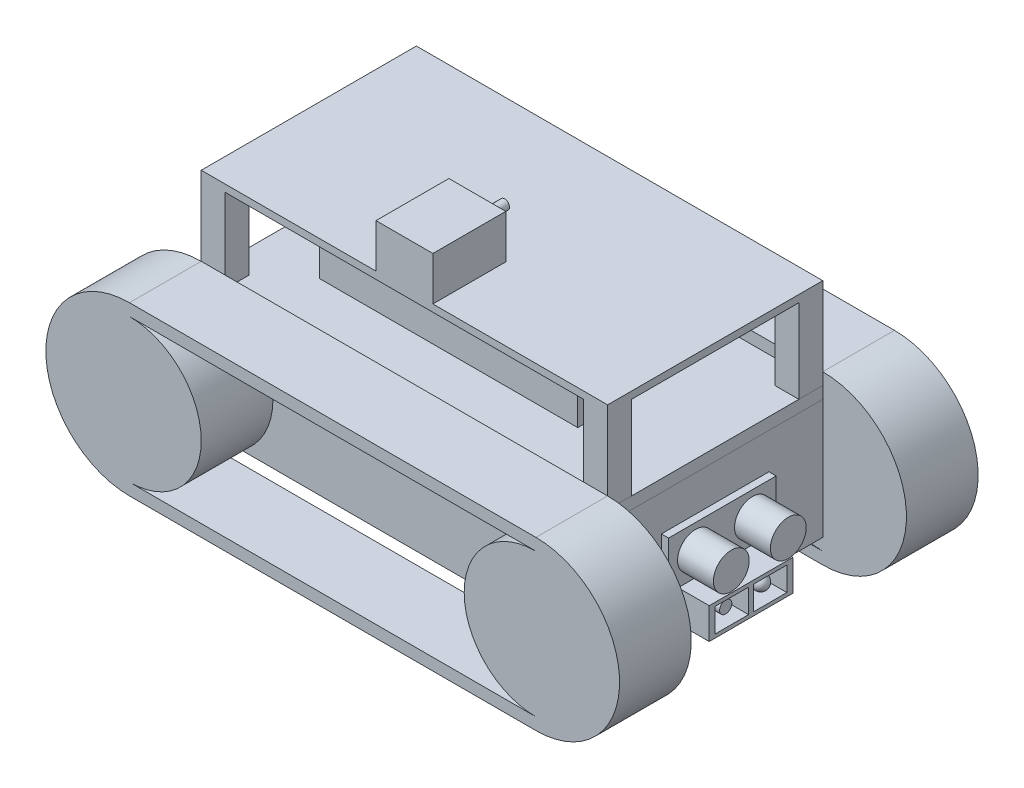
SolidWorks part; units mm, degrees
ref_plane "Front Plane" through (0, 0, 0) normal (0, 0, 1) x (1, 0, 0)
ref_plane "Top Plane" through (0, 0, 0) normal (0, 1, 0) x (1, 0, 0)
ref_plane "Right Plane" through (0, 0, 0) normal (1, 0, 0) x (0, 0, -1)
sketch "Sketch1" plane through (0, 0, 0) normal (0, 1, 0) x (1, 0, 0)
  line L1 (0, 0) -> (170, 0)
  line L2 (0, 0) -> (0, 90)
  line L3 (0, 90) -> (170, 90)
  line L4 (170, 0) -> (170, 90)
  dimension "D1" = 170
  dimension "D2" = 90
extrude "Boss-Extrude1" add sketch "Sketch1" along normal blind 50 contours L3 L4 L1 L2
sketch "Sketch2" plane through (0, 0, 0) normal (0, 0, 1) x (1, 0, 0)
  line L0 (170, 50) -> (170, 0) construction
  line L1 (0, 50) -> (0, 0) construction
  circle A0 centre (170, 25) radius 30
  circle A1 centre (0, 25) radius 30
  dimension "D1" = 60
  dimension "D2" = 60
extrude "Boss-Extrude2" add sketch "Sketch2" along normal blind 30
pattern_linear "LPattern1" count 2 spacing 120 along (0, 0, -1) of "Boss-Extrude2"
sketch "Sketch3" plane through (0, 0, 30) normal (0, 0, 1) x (1, 0, 0)
  line L0 (0, 60) -> (170, 60)
  line L1 (0, -10) -> (170, -10)
  line L2 (170, 55) -> (0, 55)
  line L3 (0, -5) -> (170, -5)
  circle A0 centre (170, 25) radius 35 construction
  circle A1 centre (0, 25) radius 35 construction
  circle A2 centre (0, 25) radius 30 construction
  circle A3 centre (170, 25) radius 30 construction
  arc A4 (170, 60) -> (170, -10) centre (170, 25) cw
  arc A5 (170, 55) -> (170, -5) centre (170, 25) cw
  arc A6 (0, 60) -> (0, -10) centre (0, 25) ccw
  arc A7 (0, -5) -> (0, 55) centre (0, 25) cw
  dimension "D1" = 70
  dimension "D2" = 70
extrude "Boss-Extrude3" add sketch "Sketch3" against normal blind 30
pattern_linear "LPattern2" count 2 spacing 120 along (0, 0, -1) of "Boss-Extrude3"
sketch "Sketch4" plane through (0, 50, 0) normal (0, 1, 0) x (1, 0, 0)
  line L1 (0, 90) -> (170, 90)
  line L2 (0, 90) -> (0, 0)
  line L3 (0, 0) -> (170, 0)
  line L4 (170, 90) -> (170, 0)
extrude "Boss-Extrude6" add sketch "Sketch4" along normal blind 5 separate body
sketch "Sketch5" plane through (0, 55, 0) normal (0, 1, 0) x (1, 0, 0)
  line L0 (85, 90) -> (85, 0)
  line L1 (170, 90) -> (0, 90) construction
  line L2 (170, 0) -> (0, 0) construction
  line L6 (31, 18.5) -> (139, 18.5) construction
  line L7 (31, 18.5) -> (31, 71.5) construction
  line L8 (31, 71.5) -> (139, 71.5) construction
  line L9 (139, 18.5) -> (139, 71.5) construction
  line L10 (31, 18.5) -> (139, 71.5)
  line L11 (31, 71.5) -> (139, 18.5)
  point P6 (85, 45)
  dimension "D1" = 53
  dimension "D2" = 108
ref_plane "Plane1" through (0, 60, 0) normal (0, 1, 0) x (1, 0, 0)
sketch "Sketch6" plane through (0, 60, 0) normal (0, 1, 0) x (1, 0, 0)
  line L1 (31, 71.5) -> (139, 71.5)
  line L2 (31, 71.5) -> (31, 18.5)
  line L3 (31, 18.5) -> (139, 18.5)
  line L4 (139, 71.5) -> (139, 18.5)
  line L5 (31, 71.5) -> (139, 18.5) construction
  line L6 (31, 18.5) -> (139, 71.5) construction
  point P0 (85, 45)
extrude "Boss-Extrude7" add sketch "Sketch6" along normal blind 15 separate body
ref_plane "Plane2" through (0, 90, 0) normal (0, 1, 0) x (1, 0, 0)
sketch "Sketch7" plane through (0, 90, 0) normal (0, 1, 0) x (1, 0, 0)
  line L0 (170, 0) -> (170, -30) construction
  line L1 (0, 90) -> (170, 90)
  line L2 (0, 90) -> (0, 0)
  line L3 (0, 0) -> (170, 0)
  line L4 (170, 90) -> (170, 0)
  line L5 (0, 90) -> (170, 0) construction
  line L6 (0, 0) -> (170, 90) construction
  line L7 (205, 0) -> (170, 0) construction
  point P0 (85, 45)
extrude "Boss-Extrude8" add sketch "Sketch7" along normal blind 3 separate body
sketch "Sketch8" plane through (0, 0, 0) normal (0, 0, 1) x (1, 0, 0)
  line L0 (85, 93) -> (85, 111.3) construction
  line L1 (0, 93) -> (170, 93) construction
  line L3 (73.1, 111.3) -> (96.9, 111.3)
  line L4 (73.1, 111.3) -> (73.1, 93)
  line L5 (73.1, 93) -> (96.9, 93)
  line L6 (96.9, 111.3) -> (96.9, 93)
  line L7 (73.1, 111.3) -> (96.9, 93) construction
  line L8 (73.1, 93) -> (96.9, 111.3) construction
  point P4 (85, 102.15)
  dimension "D1" = 18.3
  dimension "D2" = 23.8
extrude "Boss-Extrude9" add sketch "Sketch8" against normal blind 30.5
sketch "Sketch9" plane through (0, 0, -30.5) normal (0, 0, -1) x (-1, 0, 0)
  line L0 (-85, 111.3) -> (-85, 93) construction
  line L1 (-96.9, 111.3) -> (-73.1, 111.3) construction
  line L2 (-73.1, 93) -> (-96.9, 93) construction
  circle A0 centre (-85, 102.15) radius 2.0061
extrude "Boss-Extrude10" add sketch "Sketch9" along normal blind 11.45
sketch "Sketch10" plane through (170, 0, 0) normal (1, 0, 0) x (0, 0, -1)
  line L0 (45, 50) -> (45, 0) construction
  line L1 (0, 50) -> (90, 50) construction
  line L2 (0, 0) -> (90, 0) construction
  line L4 (22.5, 35) -> (67.5, 35)
  line L5 (22.5, 35) -> (22.5, 15)
  line L6 (22.5, 15) -> (67.5, 15)
  line L7 (67.5, 35) -> (67.5, 15)
  line L8 (22.5, 35) -> (67.5, 15) construction
  line L9 (22.5, 15) -> (67.5, 35) construction
  point P6 (45, 25)
  dimension "D1" = 20
  dimension "D2" = 45
extrude "Boss-Extrude11" add sketch "Sketch10" along normal blind 3
sketch "Sketch11" plane through (173, 0, 0) normal (1, 0, 0) x (0, 0, -1)
  line L0 (45, 35) -> (45, 15) construction
  line L1 (67.5, 35) -> (22.5, 35) construction
  line L2 (22.5, 15) -> (67.5, 15) construction
  line L3 (45, 25) -> (22.5, 25) construction
  line L4 (22.5, 35) -> (22.5, 15) construction
  line L5 (45, 25) -> (67.5, 25) construction
  line L6 (67.5, 15) -> (67.5, 35) construction
  circle A0 centre (57.5882, 25) radius 7.5
  circle A1 centre (33.75, 25) radius 7.5
  dimension "D1" = 15
  dimension "D2" = 15
extrude "Boss-Extrude12" add sketch "Sketch11" along normal blind 15
sketch "Sketch12" plane through (170, 0, 0) normal (1, 0, 0) x (0, 0, -1)
  line L0 (45, 15) -> (45, 0) construction
  line L1 (22.5, 15) -> (67.5, 15) construction
  line L2 (0, 0) -> (90, 0) construction
  line L3 (30, 12.5) -> (44, 12.5)
  line L4 (30, 12.5) -> (60, 12.5) construction
  line L5 (30, 12.5) -> (30, 2.5)
  line L6 (30, 2.5) -> (60, 2.5) construction
  line L7 (60, 12.5) -> (60, 2.5)
  line L8 (30, 12.5) -> (60, 2.5) construction
  line L9 (30, 2.5) -> (60, 12.5) construction
  line L10 (27.5, 14) -> (62.5, 14)
  line L11 (27.5, 14) -> (27.5, 1)
  line L12 (27.5, 1) -> (62.5, 1)
  line L13 (62.5, 14) -> (62.5, 1)
  line L14 (27.5, 14) -> (62.5, 1) construction
  line L15 (27.5, 1) -> (62.5, 14) construction
  line L16 (44, 12.5) -> (46, 12.5) construction
  line L17 (44, 12.5) -> (44, 2.5)
  line L18 (44, 2.5) -> (46, 2.5) construction
  line L19 (46, 12.5) -> (46, 2.5)
  line L20 (44, 12.5) -> (46, 2.5) construction
  line L21 (44, 2.5) -> (46, 12.5) construction
  line L22 (60, 12.5) -> (46, 12.5)
  line L23 (46, 2.5) -> (60, 2.5)
  line L24 (30, 2.5) -> (44, 2.5)
  point P6 (45, 7.5)
  point P11 (45, 7.5)
  point P16 (45, 7.5)
  dimension "D1" = 30
  dimension "D2" = 10
  dimension "D3" = 35
  dimension "D4" = 13
  dimension "D5" = 2
extrude "Boss-Extrude13" add sketch "Sketch12" along normal blind 15
ref_plane "Plane3" through (180, 0, 0) normal (1, 0, 0) x (0, 0, -1)
sketch "Sketch13" plane through (180, 0, 0) normal (1, 0, 0) x (0, 0, -1)
  line L0 (37, 12.5) -> (37, 2.5) construction
  line L1 (44, 12.5) -> (30, 12.5) construction
  line L2 (30, 2.5) -> (44, 2.5) construction
  circle A0 centre (37, 7.5) radius 2.55
  dimension "D1" = 5.1
extrude "Boss-Extrude14" add sketch "Sketch13" along normal blind 2.4 separate body
ref_plane "Plane4" through (175.4, 0, 0) normal (1, 0, 0) x (0, 0, -1)
sketch "Sketch14" plane through (175.4, 0, 0) normal (1, 0, 0) x (0, 0, -1)
  line L0 (53, 12.5) -> (53, 2.5) construction
  line L1 (60, 12.5) -> (46, 12.5) construction
  line L2 (46, 2.5) -> (60, 2.5) construction
  circle A0 centre (53, 7.8643) radius 3
  dimension "D1" = 6
extrude "Boss-Extrude15" add sketch "Sketch14" along normal blind 8.6 separate body contours A0
fillet "Fillet1" radius 3 1 edges at (184, 7.8643, -56)
sketch "Sketch15" plane through (0, 0, 0) normal (-1, 0, 0) x (0, 0, 1)
  line L0 (-45, 0) -> (-45, 15) construction
  line L1 (0, 0) -> (-90, 0) construction
  line L3 (-62.5, 15) -> (-27.5, 15)
  line L4 (-62.5, 15) -> (-62.5, 0)
  line L5 (-62.5, 0) -> (-27.5, 0)
  line L6 (-27.5, 15) -> (-27.5, 0)
  line L7 (-62.5, 15) -> (-27.5, 0) construction
  line L8 (-62.5, 0) -> (-27.5, 15) construction
  point P4 (-45, 7.5)
  dimension "D1" = 15
  dimension "D2" = 35
extrude "Boss-Extrude16" add sketch "Sketch15" along normal blind 13
sketch "Sketch17" plane through (0, 0, 0) normal (0, -1, 0) x (1, 0, 0)
  line L0 (0, -62.5) -> (0, -90) construction
  line L1 (-13, -27.5) -> (0, -27.5) construction
  line L2 (-13, -27.5) -> (-13, -62.5) construction
  line L3 (-13, -62.5) -> (0, -62.5) construction
  line L4 (0, -27.5) -> (0, -62.5) construction
  line L5 (0, -45) -> (-13, -45) construction
  line L7 (-11.5, -60) -> (-1.5, -60)
  line L8 (-11.5, -60) -> (-11.5, -30)
  line L9 (-11.5, -30) -> (-1.5, -30)
  line L10 (-1.5, -60) -> (-1.5, -30)
  line L11 (-11.5, -60) -> (-1.5, -30) construction
  line L12 (-11.5, -30) -> (-1.5, -60) construction
  point P9 (-6.5, -45)
  dimension "D1" = 30
  dimension "D2" = 10
extrude "Cut-Extrude1" cut sketch "Sketch17" against normal blind 12 contours L8 L9 L10 L7
sketch "Sketch18" plane through (0, 12, 0) normal (0, -1, 0) x (1, 0, 0)
  line L0 (-11.5, -44.4175) -> (-1.5, -44.4175) construction
  line L1 (-11.5, -60) -> (-11.5, -30) construction
  line L2 (-1.5, -60) -> (-1.5, -30) construction
  line L4 (-11.5, -43.4175) -> (-1.5, -43.4175)
  line L5 (-11.5, -43.4175) -> (-11.5, -45.4175)
  line L6 (-11.5, -45.4175) -> (-1.5, -45.4175)
  line L7 (-1.5, -43.4175) -> (-1.5, -45.4175)
  line L8 (-11.5, -43.4175) -> (-1.5, -45.4175) construction
  line L9 (-11.5, -45.4175) -> (-1.5, -43.4175) construction
  point P6 (-6.5, -44.4175)
  dimension "D1" = 2
extrude "Boss-Extrude17" add sketch "Sketch18" along normal blind 12
sketch "Sketch20" plane through (0, 90, 0) normal (0, -1, 0) x (1, 0, 0)
  line L1 (0, 0) -> (10, 0)
  line L2 (0, 0) -> (0, -10)
  line L3 (0, -10) -> (10, -10)
  line L4 (10, 0) -> (10, -10)
  line L5 (170, 0) -> (170, -90) construction
  line L6 (170, 0) -> (160, 0)
  line L7 (170, 0) -> (170, -10)
  line L8 (170, -10) -> (160, -10)
  line L11 (160, 0) -> (160, -10)
  line L12 (0, 0) -> (170, 0) construction
  line L13 (170, -90) -> (0, -90) construction
  line L14 (170, -90) -> (160, -90)
  line L16 (170, -90) -> (170, -80)
  line L17 (170, -80) -> (160, -80)
  line L18 (160, -90) -> (160, -80)
  line L19 (0, -90) -> (0, 0) construction
  line L20 (0, -90) -> (10, -90)
  line L21 (0, -90) -> (0, -80)
  line L22 (0, -80) -> (10, -80)
  line L23 (10, -90) -> (10, -80)
  dimension "D1" = 10
  dimension "D2" = 10
  dimension "D3" = 10
  dimension "D4" = 10
extrude "Boss-Extrude20" add sketch "Sketch20" along normal blind 35
ref_plane "Plane5" through (0, 0, 0) normal (0, -1, 0) x (-1, 0, 0)
sketch "Sketch21" plane through (0, 0, 0) normal (0, -1, 0) x (-1, 0, 0)
  line L0 (6.5, 60) -> (6.5, 45.4175) construction
  line L1 (11.5, 60) -> (1.5, 60) construction
  line L2 (11.5, 45.4175) -> (1.5, 45.4175) construction
  circle A0 centre (6.5, 52.4581) radius 2.55
  dimension "D1" = 5.1
extrude "Boss-Extrude21" add sketch "Sketch21" against normal blind 2.4 separate body
ref_plane "Plane6" through (0, 0, 0) normal (0, -1, 0) x (-1, 0, 0)
sketch "Sketch24" plane through (0, 0, 0) normal (0, -1, 0) x (-1, 0, 0)
  line L0 (6.5, 30) -> (6.5, 43.4175) construction
  line L1 (11.5, 30) -> (1.5, 30) construction
  line L2 (1.5, 43.4175) -> (11.5, 43.4175) construction
  circle A0 centre (6.5, 36.7088) radius 3
  dimension "D1" = 6
extrude "Boss-Extrude22" add sketch "Sketch24" against normal blind 6 separate body contours A0
fillet "Fillet2" radius 3 1 edges at (-6.5, 0, -39.7088)
